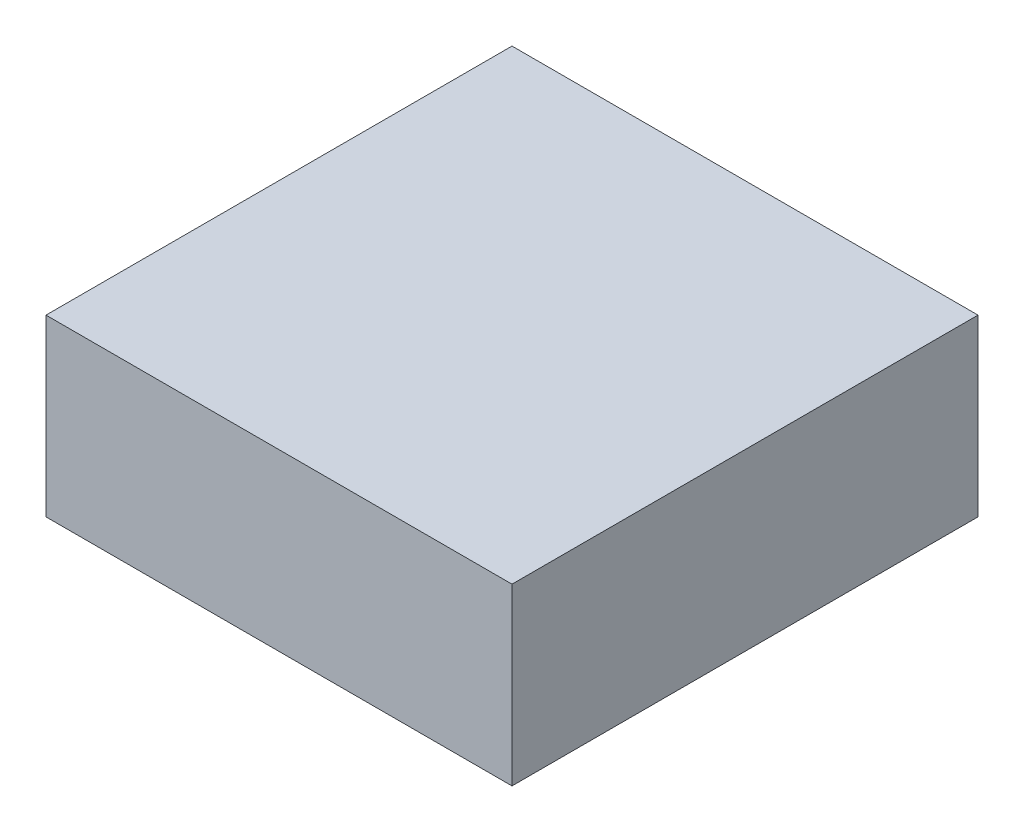
SolidWorks part; units mm, degrees
ref_plane "Front Plane" through (0, 0, 0) normal (0, 0, 1) x (1, 0, 0)
ref_plane "Top Plane" through (0, 0, 0) normal (0, 1, 0) x (1, 0, 0)
ref_plane "Right Plane" through (0, 0, 0) normal (1, 0, 0) x (0, 0, -1)
sketch "Sketch1" plane through (0, 0, 0) normal (0, 1, 0) x (1, 0, 0)
  line L1 (-16, 16) -> (16, 16)
  line L2 (-16, 16) -> (-16, -16)
  line L3 (-16, -16) -> (16, -16)
  line L4 (16, 16) -> (16, -16)
  line L5 (-16, 16) -> (16, -16) construction
  line L6 (-16, -16) -> (16, 16) construction
  point P0 (0, 0)
  dimension "D1" = 32
  dimension "D2" = 32
extrude "Boss-Extrude1" add sketch "Sketch1" along normal blind 12
